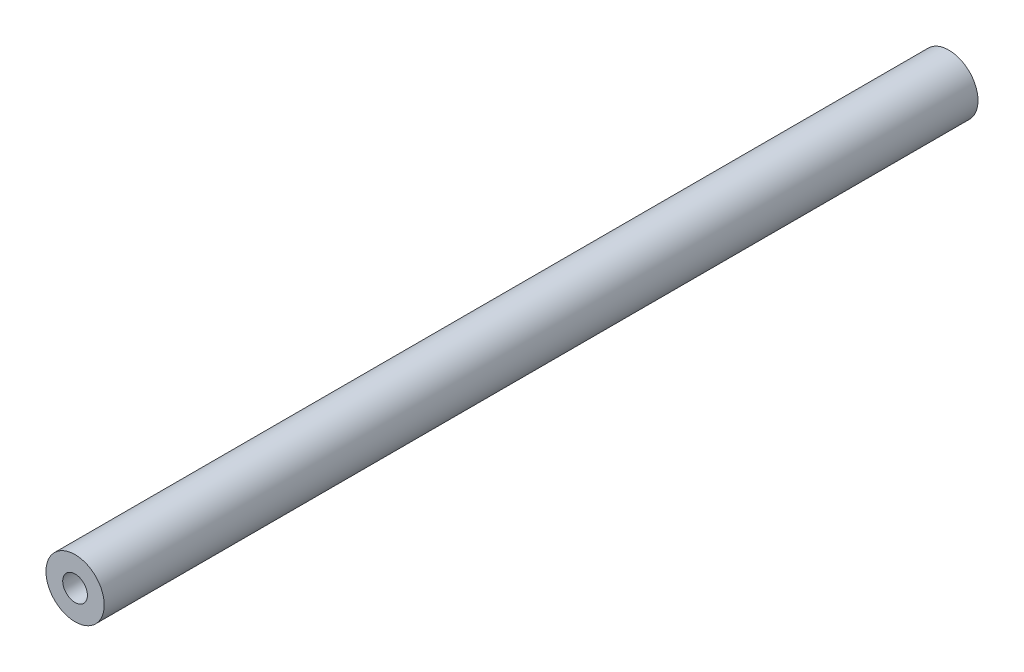
SolidWorks part; units mm, degrees
material "6061-T6 (SS)"
ref_plane "Front Plane" through (0, 0, 0) normal (0, 0, 1) x (1, 0, 0)
ref_plane "Top Plane" through (0, 0, 0) normal (0, 1, 0) x (1, 0, 0)
ref_plane "Right Plane" through (0, 0, 0) normal (1, 0, 0) x (0, 0, -1)
sketch "Sketch1" plane through (0, 0, 0) normal (0, 0, 1) x (1, 0, 0)
  circle A0 centre (0, 0) radius 4.7625
  dimension "D1" = 9.525
extrude "Boss-Extrude1" add sketch "Sketch1" along normal mid plane 142.875
hole_wizard "#10-32 Tapped Hole1" positions "3DSketch1" profile "Sketch2" tap size "#10-32" standard "ANSI Inch"
sketch3d "3DSketch1"
  line L0 (0, 0, 71.4375) -> (0, 0, -71.4375) construction
  point P0 (0, 0, 71.4375)
  point P4 (0, 0, -71.4375)
sketch "Sketch2" plane through (0, 0, 71.4375) normal (1, 0, 0) x (0, -1, 0)
  line L0 (0, 0) -> (0, 13.1513)
  line L1 (0, 13.1513) -> (2.0193, 11.938)
  line L2 (2.0193, 11.938) -> (2.0193, 0)
  line L5 (2.0193, 0) -> (0, 0)
  line L10 (0, 13.1513) -> (-2.0193, 11.938) construction
  line L11 (0, -6.35) -> (0, 107.95) construction
  dimension "Tap Drill Dia." = 4.0386
  dimension "Tap Drill Depth" = 11.938
  dimension "Drill Angle" = 118
cosmetic thread "Hole Thread1"
cosmetic thread "Hole Thread2"
